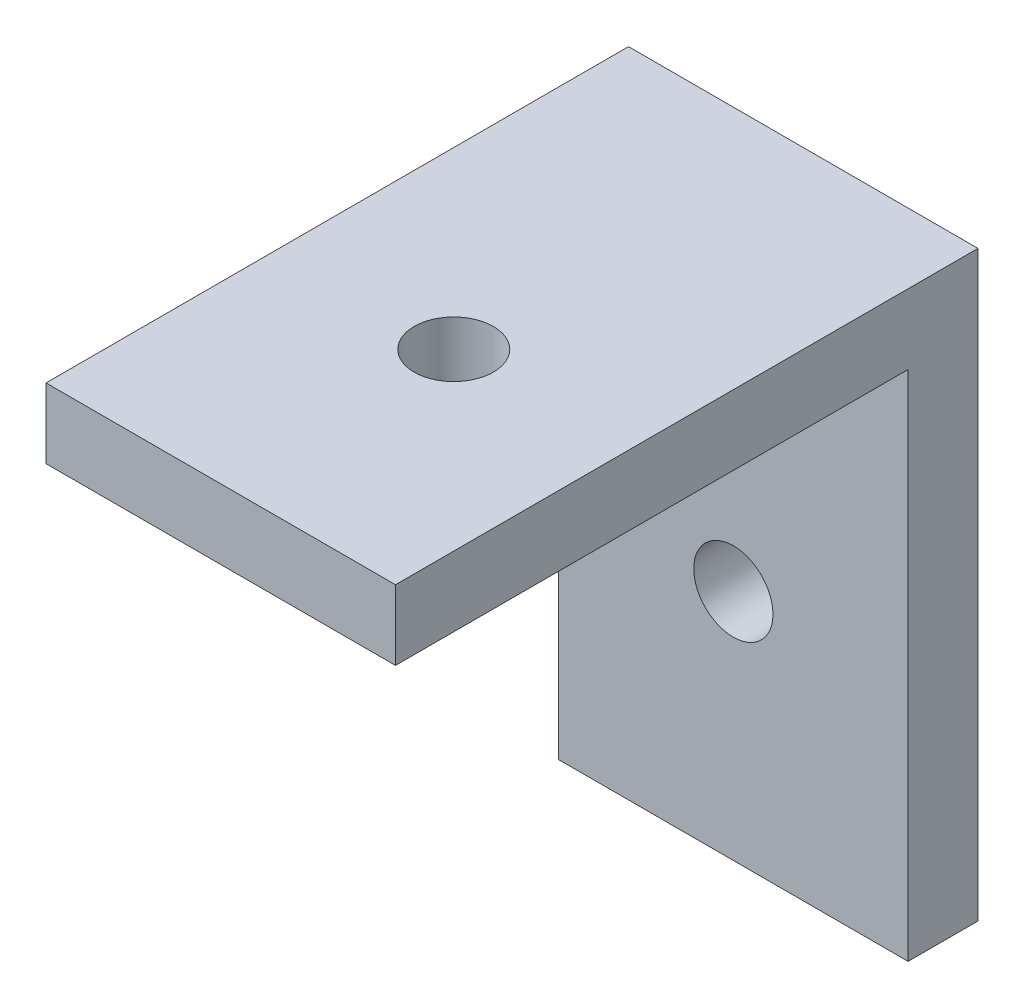
SolidWorks part; units mm, degrees
material "Aleación 6061"
ref_plane "Alzado" through (0, 0, 0) normal (0, 0, 1) x (1, 0, 0)
ref_plane "Planta" through (0, 0, 0) normal (0, 1, 0) x (1, 0, 0)
ref_plane "Vista lateral" through (0, 0, 0) normal (1, 0, 0) x (0, 0, -1)
sketch "Croquis1" plane through (0, 0, 0) normal (0, 0, 1) x (1, 0, 0)
  line L1 (-7.5, -25) -> (7.5, -25)
  line L2 (-7.5, -25) -> (-7.5, 0)
  line L3 (-7.5, 0) -> (7.5, 0)
  line L4 (7.5, -25) -> (7.5, 0)
  dimension "D1" = 7.5
  dimension "D2" = 25
  dimension "D3" = 7.5
  dimension "D4" = 25
  dimension "D5" = 7.5
  dimension "D6" = 7.5
extrude "Ala_horizontal" add sketch "Croquis1" along normal blind 3
sketch "Croquis2" plane through (0, 0, 0) normal (0, 1, 0) x (1, 0, 0)
  line L1 (-7.5, 0) -> (7.5, 0)
  line L2 (-7.5, 0) -> (-7.5, -25)
  line L3 (-7.5, -25) -> (7.5, -25)
  line L4 (7.5, 0) -> (7.5, -25)
  dimension "D1" = 7.5
  dimension "D2" = 7.5
  dimension "D3" = 7.5
  dimension "D4" = 25
  dimension "D5" = 7.5
  dimension "D6" = 25
extrude "Ala_vertical" add sketch "Croquis2" along normal blind 3 from offset 3
sketch "Croquis3" plane through (0, 0, 0) normal (0, 0, 1) x (1, 0, 0)
  circle A0 centre (0, -15) radius 1.7
  dimension "D1" = 3.4
  dimension "D2" = 15
extrude "Barreno_M3_h" cut sketch "Croquis3" along normal blind 3
sketch "Croquis4" plane through (0, 0, 0) normal (0, 1, 0) x (1, 0, 0)
  circle A0 centre (0, -15) radius 1.7
  dimension "D1" = 3.4
  dimension "D2" = 15
extrude "Barreno_M3_v" cut sketch "Croquis4" along normal blind 3 from offset 3
